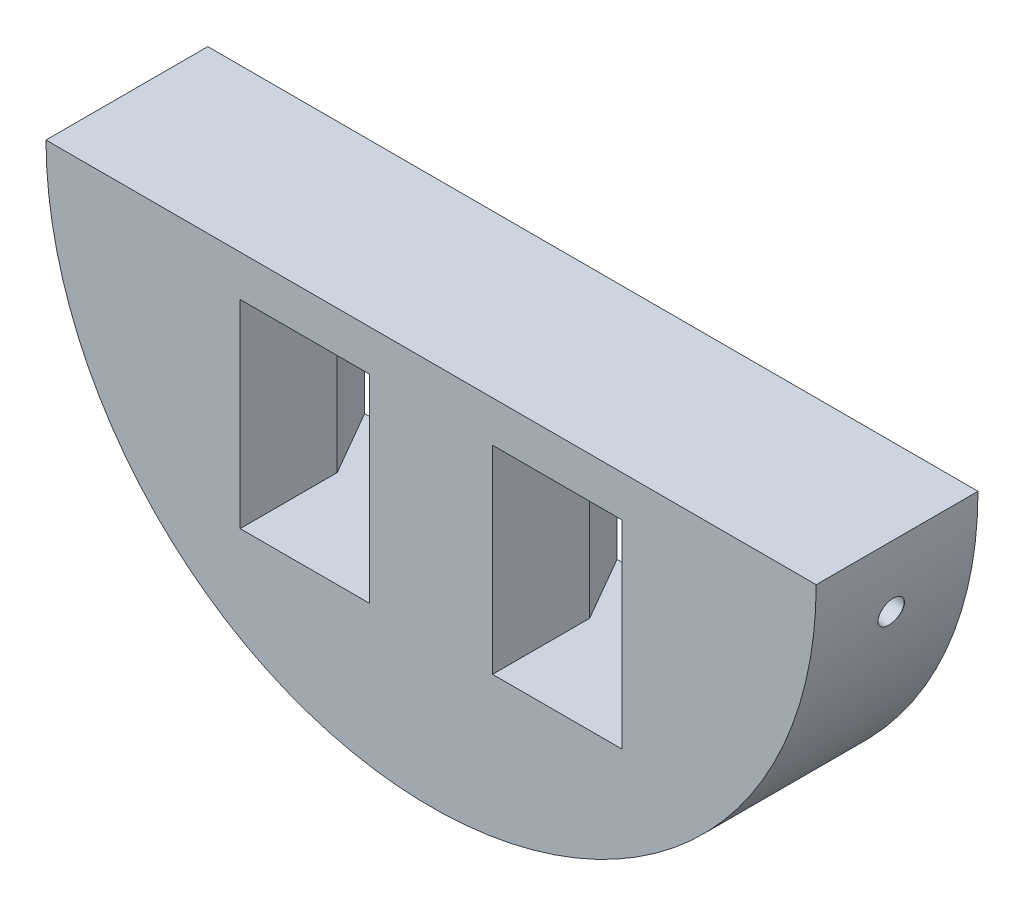
SolidWorks part; units mm, degrees
ref_plane "Front Plane" through (0, 0, 0) normal (0, 0, 1) x (1, 0, 0)
ref_plane "Top Plane" through (0, 0, 0) normal (0, 1, 0) x (1, 0, 0)
ref_plane "Right Plane" through (0, 0, 0) normal (1, 0, 0) x (0, 0, -1)
sketch "Sketch1" plane through (0, 0, 0) normal (0, 0, 1) x (1, 0, 0)
  line L0 (-119, 0) -> (0, 0)
  line L3 (-50, -37) -> (-30, -37)
  line L4 (-50, -37) -> (-50, -15)
  line L5 (-50, -15) -> (-30, -15)
  line L6 (-30, -37) -> (-30, -15)
  line L7 (-89, -37) -> (-69, -37)
  line L8 (-89, -37) -> (-89, -15)
  line L9 (-89, -15) -> (-69, -15)
  line L10 (-69, -37) -> (-69, -15)
  arc A1 (-119, 0) -> (0, 0) centre (-59.5, 0) ccw
  dimension "D1" = 30
  dimension "D7" = 59.5
  dimension "D2" = 15
  dimension "D3" = 30
  dimension "D4" = 20
  dimension "D5" = 22
extrude "Boss-Extrude1" add sketch "Sketch1" along normal blind 25
hole_wizard "Ø4.0mm Dowel Hole2" positions "3DSketch2" profile "Sketch4" hole size "Ø4.0" standard "ANSI Metric"
sketch3d "3DSketch2"
  line L2 (0, 0, 25) -> (0, 0, 0) construction
  line L4 (0, 0, 25) -> (0, 0, 0) construction
  line L5 (0, 0, 12.5) -> (-0.9039, -10.3321, 12.5) construction
  line L8 (-59.5, 0, 0) -> (-59.5, 0, 25) construction
  line L9 (0, 0, 0) -> (-119, 0, 0) construction
  line L10 (0, 0, 25) -> (-119, 0, 25) construction
  line L12 (-59.5, 0, 12.5) -> (-0.9039, -10.3321, 12.5) construction
  line L16 (-59.5, 0, 12.5) -> (0, 0, 12.5) construction
  point P0 (-0.9039, -10.3321, 12.5)
  point P16 (-0.9039, -10.3321, 12.5)
  point P23 (-0.9039, -10.3321, 12.5)
  point P25 (-0.9039, -10.3321, 12.5)
  dimension "D1" = 10
sketch "Sketch4" plane through (-0.9039, -10.3321, 12.5) normal (0, 0, 1) x (0.1736, 0.9848, 0)
  line L0 (0, 0) -> (0, 11.2017)
  line L1 (0, 11.2017) -> (2, 10)
  line L2 (2, 10) -> (2, 0.025)
  line L3 (2, 0.025) -> (2.025, 0)
  line L5 (2.025, 0) -> (0, 0)
  line L6 (-2, 0.025) -> (-2.025, 0) construction
  line L10 (0, 11.2017) -> (-2, 10) construction
  line L11 (0, -6.35) -> (0, 107.95) construction
  dimension "Hole Dia." = 4
  dimension "Hole Depth" = 10
  dimension "Near C'Sink Dia." = 4.05
  dimension "Near C'Sink Angle" = 90
  dimension "Drill Angle" = 118
pattern_circular "CirPattern1" count 5 over 160 about axis through (-59.5, 0, 0) along (0, 0, 1) of "Ø4.0mm Dowel Hole2"
chamfer "Chamfer1" distance 15 angle 30 2 edges at (-79, -15, 25) (-40, -15, 25)
chamfer "Chamfer2" distance 10 angle 30 4 edges at (-50, -26, 0) (-30, -26, 0) (-89, -26, 0) (-69, -26, 0)
